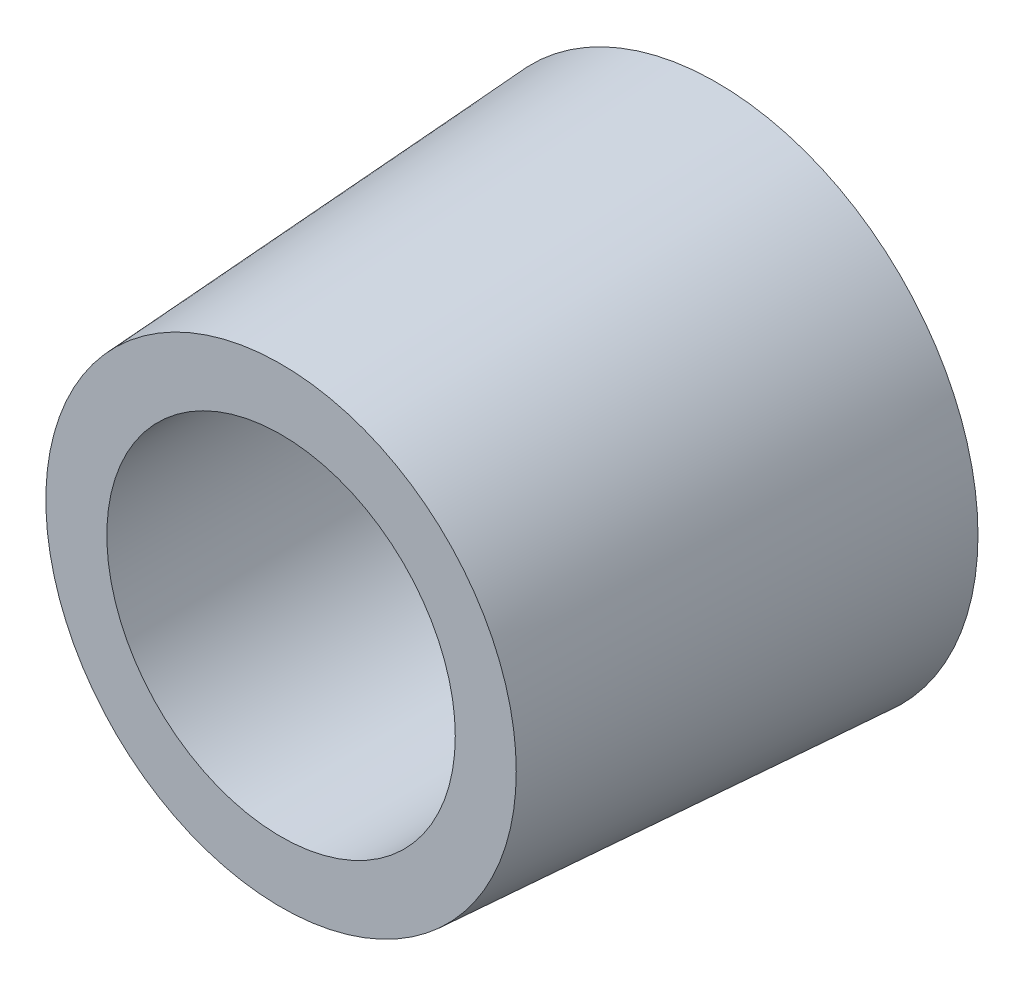
SolidWorks part; units mm, degrees
material "Mosiądz"
ref_plane "Płaszczyzna przednia" through (0, 0, 0) normal (0, 0, 1) x (1, 0, 0)
ref_plane "Płaszczyzna górna" through (0, 0, 0) normal (0, 1, 0) x (1, 0, 0)
ref_plane "Płaszczyzna prawa" through (0, 0, 0) normal (1, 0, 0) x (0, 0, -1)
sketch "Szkic1" plane through (0, 0, 0) normal (0, 0, 1) x (1, 0, 0)
  circle A0 centre (0, 0) radius 3
  dimension "D1" = 6
ref_plane "Płaszczyzna1" through (0, 0, 5) normal (0, 0, 1) x (1, 0, 0)
sketch "Szkic2" plane through (0, 0, 5) normal (0, 0, 1) x (1, 0, 0)
  circle A0 centre (0, 0) radius 2.7
  dimension "D1" = 5.4
loft "Wyciągnięcie po profilach1" add profiles "Szkic1", "Szkic2"
sketch "Szkic3" plane through (0, 0, 5) normal (0, 0, 1) x (1, 0, 0)
  circle A0 centre (0, 0) radius 2
  dimension "D1" = 4
extrude "Wytnij-wyciągnięcie1" cut sketch "Szkic3" against normal blind 10
